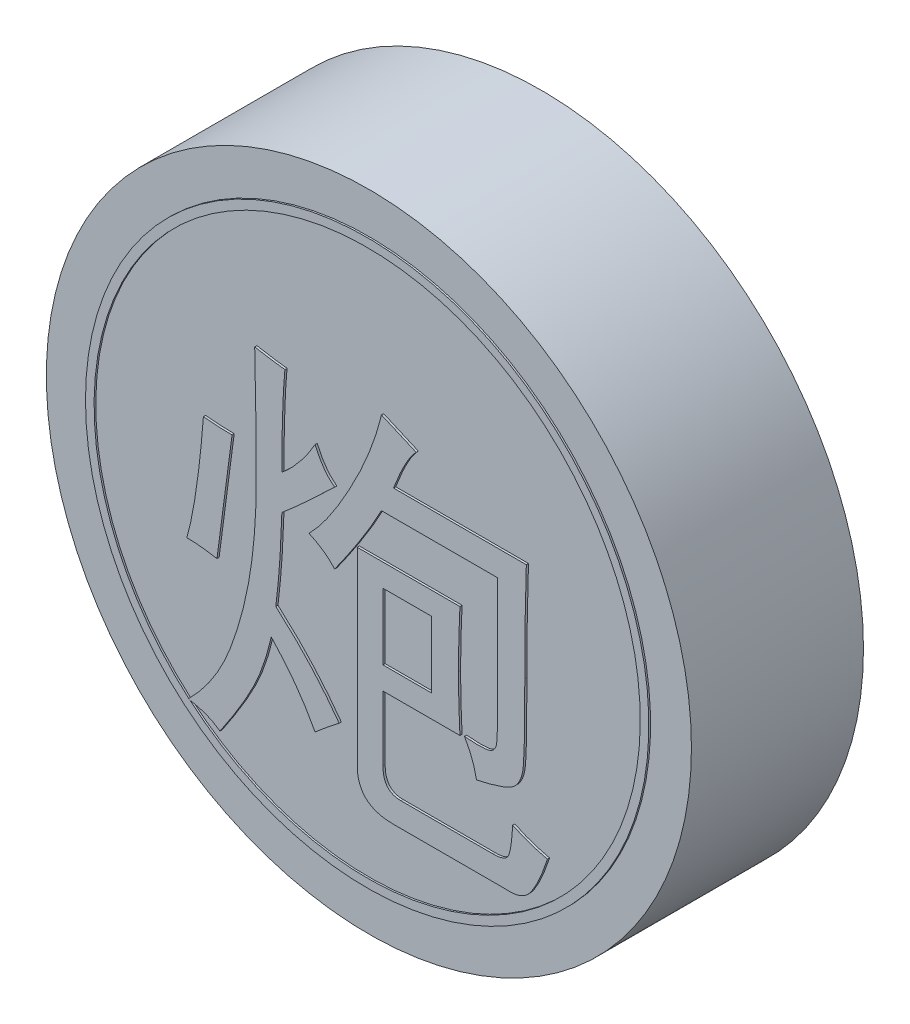
SolidWorks part; units mm, degrees
ref_plane "前视基准面" through (0, 0, 0) normal (0, 0, 1) x (1, 0, 0)
ref_plane "上视基准面" through (0, 0, 0) normal (0, 1, 0) x (1, 0, 0)
ref_plane "右视基准面" through (0, 0, 0) normal (1, 0, 0) x (0, 0, -1)
other "Configuration Table"
sketch "草图1" plane through (0, 0, 0) normal (0, 0, 1) x (1, 0, 0)
  circle A0 centre (0, 0) radius 15
  dimension "D1" = 30
extrude "Diameter30_Height8" add sketch "草图1" against normal blind 8
sketch "草图2" plane through (0, 0, 0) normal (0, 0, 1) x (1, 0, 0)
  text T0 "炮" font "SimHei" height 12
extrude "Character_炮" add sketch "草图2" along normal blind 0.1
sketch "草图3" plane through (0, 0, 0) normal (0, 0, 1) x (1, 0, 0)
  circle A0 centre (0, 0) radius 13.1
  circle A1 centre (0, 0) radius 12.7
extrude "Ink_ring" add sketch "草图3" along normal blind 0.08
